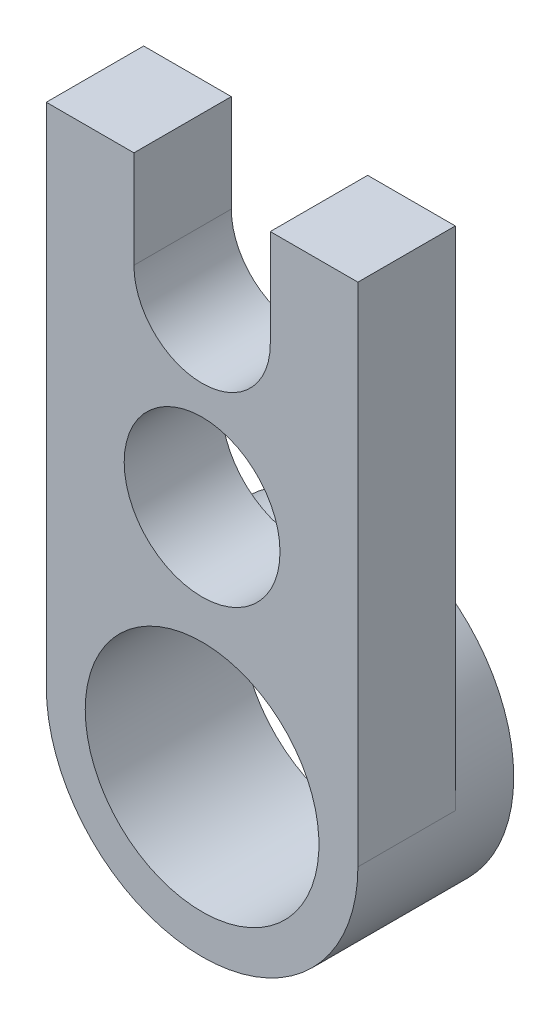
SolidWorks part; units mm, degrees
ref_plane "Plan1" through (0, 0, 0) normal (0, 0, 1) x (1, 0, 0)
ref_plane "Plan2" through (0, 0, 0) normal (0, 1, 0) x (1, 0, 0)
ref_plane "Plan3" through (0, 0, 0) normal (1, 0, 0) x (0, 0, -1)
sketch "Esquisse1" plane through (0, 0, 0) normal (0, 0, 1) x (1, 0, 0)
  line L0 (-25.7428, 26) -> (-30.2428, 26)
  line L1 (-30.2428, 0) -> (-30.2428, 26)
  line L2 (-14.2428, 26) -> (-18.7428, 26)
  line L3 (-14.2428, 26) -> (-14.2428, 0)
  line L4 (-18.7428, 21) -> (-18.7428, 26)
  line L5 (-25.7428, 21) -> (-25.7428, 26)
  arc A0 (-14.2428, 0) -> (-30.2428, 0) centre (-22.2428, 0) cw
  circle A2 centre (-22.2428, 12) radius 4
  arc A3 (-25.7428, 21) -> (-18.7428, 21) centre (-22.2428, 21) ccw
  dimension "D2" = 8
  dimension "D4" = 7
  dimension "D1" = 16
  dimension "D3" = 12
  dimension "D5" = 21
  dimension "D6" = 5
extrude "Base-Extrusion" add sketch "Esquisse1" along normal blind 5
sketch "Esquisse2" plane through (0, 0, 5) normal (0, 0, 1) x (1, 0, 0)
  circle A0 centre (-22.2428, 0) radius 8
  dimension "D1" = 16
extrude "Boss.-Extru.1" add sketch "Esquisse2" against normal blind 8
hole_wizard "Perçage1" positions "Esquisse4" profile "Esquisse3" legacy
sketch "Esquisse4" plane through (0, 0, -3) normal (0, 0, -1) x (-1, 0, 0)
  point P0 (22.2428, 0)
sketch "Esquisse3" plane through (-22.2428, 0, -3) normal (1, 0, 0) x (0, 1, 0)
  line L0 (0, 0) -> (0, 11.6052)
  line L1 (0, 11.6052) -> (6, 8)
  line L2 (6, 8) -> (6, 0)
  line L4 (6, 0) -> (0, 0)
  line L6 (0, 11.6052) -> (-6, 8) construction
  line L7 (0, -4.2442) -> (0, 117.3081) construction
  dimension "Diamètre" = 12
  dimension "Profondeur" = 8
  dimension "Angle" = 118
